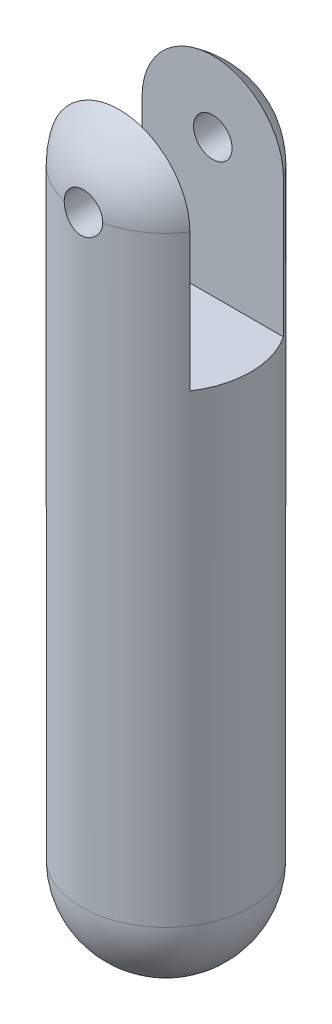
SolidWorks part; units mm, degrees
ref_plane "Front Plane" through (0, 0, 0) normal (0, 0, 1) x (1, 0, 0)
ref_plane "Top Plane" through (0, 0, 0) normal (0, 1, 0) x (1, 0, 0)
ref_plane "Right Plane" through (0, 0, 0) normal (1, 0, 0) x (0, 0, -1)
sketch "Sketch1" plane through (0, 0, 0) normal (0, 0, 1) x (1, 0, 0)
  line L0 (0, 0) -> (0, -13.8684) construction
  line L1 (1.9558, 0) -> (1.9558, -13.8684)
  line L2 (-1.9558, 0) -> (-1.9558, -13.8684)
  line L3 (-1.9558, -0.4445) -> (1.9558, -0.4445) construction
  line L4 (0, -0.4445) -> (0, -15.8242)
  line L5 (0, -0.4445) -> (0, 1.9558)
  arc A0 (1.9558, 0) -> (-1.9558, 0) centre (0, 0) ccw
  arc A1 (-1.9558, -13.8684) -> (1.9558, -13.8684) centre (0, -13.8684) ccw
  circle A2 centre (0, 0) radius 0.4445 construction
  point P3 (0, -6.9342)
  dimension "D1" = 1.9558
  dimension "D2" = 17.78
  dimension "D3" = 0.889
  dimension "D4" = 13.8684
revolve "Revolve1" add sketch "Sketch1" angle 360 about L0
sketch "Sketch2" plane through (0, 0, 0) normal (1, 0, 0) x (0, 0, -1)
  line L0 (0, -0.4445) -> (0, 1.9558) construction
  line L1 (0, -0.4445) -> (0, 1.9558)
  line L2 (0, 0) -> (0, -3.175)
  line L3 (1.0795, 2.1394) -> (-1.0795, 2.1394)
  line L4 (1.0795, 2.1394) -> (1.0795, -3.175)
  line L5 (1.0795, -3.175) -> (-1.0795, -3.175)
  line L6 (-1.0795, 2.1394) -> (-1.0795, -3.175)
  line L7 (1.0795, 2.1394) -> (-1.0795, -3.175) construction
  line L8 (1.0795, -3.175) -> (-1.0795, 2.1394) construction
  line L9 (0, -0.4445) -> (0, -15.8242) construction
  point P2 (0, -0.5178)
  dimension "D1" = 2.159
  dimension "D3" = 3.175
extrude "Cut-Extrude1" cut sketch "Sketch2" against normal through all and the other way through all contours L3 L6 L5 L4
sketch "Sketch3" plane through (0, 0, 0) normal (0, 0, 1) x (1, 0, 0)
  circle A0 centre (0, 0) radius 0.4445 construction
  circle A1 centre (0, 0) radius 0.4445
extrude "Cut-Extrude2" cut sketch "Sketch3" against normal through all and the other way through all
ref_plane "Plane2" through (0, -13.8684, 0) normal (0, -1, 0) x (-1, 0, 0)
